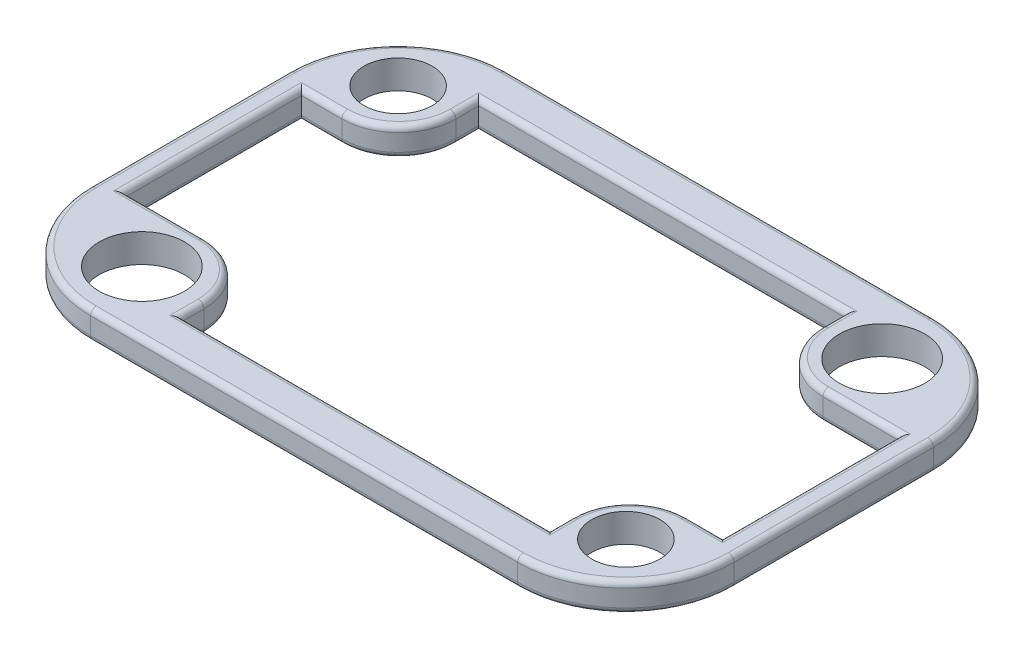
SolidWorks part; units mm, degrees
ref_plane "Alzado" through (0, 0, 0) normal (0, 0, 1) x (1, 0, 0)
ref_plane "Planta" through (0, 0, 0) normal (0, 1, 0) x (1, 0, 0)
ref_plane "Vista lateral" through (0, 0, 0) normal (1, 0, 0) x (0, 0, -1)
sketch "Sketch1" plane through (0, 0, 0) normal (0, 1, 0) x (1, 0, 0)
  line L1 (-57.5, 37.5) -> (57.5, 37.5)
  line L2 (-57.5, 37.5) -> (-57.5, -37.5)
  line L3 (-57.5, -37.5) -> (57.5, -37.5)
  line L4 (57.5, 37.5) -> (57.5, -37.5)
  circle A0 centre (-44.48, 24.48) radius 6
  circle A1 centre (44.48, -24.48) radius 6
  point P0 (0, 0)
  dimension "D6" = 12
  dimension "D10" = 12
  dimension "D1" = 75
  dimension "D2" = 115
  dimension "D3" = 37.5
  dimension "D4" = 57.5
  dimension "D5" = 13.02
  dimension "D7" = 13.02
  dimension "D8" = 13.02
  dimension "D9" = 13.02
extrude "Boss-Extrude1" add sketch "Sketch1" along normal blind 5
sketch "Sketch2" plane through (0, 5, 0) normal (0, 1, 0) x (1, 0, 0)
  line L0 (57.5, 37.5) -> (-57.5, 37.5) construction
  line L1 (-57.5, 37.5) -> (-57.5, -37.5) construction
  line L2 (57.5, -37.5) -> (57.5, 37.5) construction
  line L4 (-57.3874, 0) -> (58.0842, 0) construction
  line L5 (-41.5, 15.5) -> (41.5, 15.5)
  line L6 (-51.5, 5.5) -> (-51.5, -5.5)
  line L7 (-41.5, -15.5) -> (41.5, -15.5)
  line L8 (51.5, 5.5) -> (51.5, -5.5)
  line L9 (-51.5, 15.5) -> (51.5, -15.5) construction
  line L10 (-51.5, -15.5) -> (51.5, 15.5) construction
  arc A5 (41.5, -15.5) -> (51.5, -5.5) centre (41.5, -5.5) ccw
  arc A6 (41.5, 15.5) -> (51.5, 5.5) centre (41.5, 5.5) cw
  arc A7 (-51.5, -5.5) -> (-41.5, -15.5) centre (-41.5, -5.5) ccw
  arc A8 (-41.5, 15.5) -> (-51.5, 5.5) centre (-41.5, 5.5) ccw
  point P19 (0, 0)
  dimension "D18" = 10
  dimension "D15" = 6
  dimension "D16" = 6
  dimension "D17" = 22
extrude "Cut-Extrude1" cut sketch "Sketch2" against normal blind 5
fillet "Fillet1" radius 20 4 edges at (-57.5, 2.5, 37.5) (-57.5, 2.5, -37.5) (57.5, 2.5, -37.5) (57.5, 2.5, 37.5)
sketch "Sketch5" plane through (0, 0, 0) normal (0, -1, 0) x (1, 0, 0)
  line L0 (-37.5, 37.5) -> (37.5, 37.5) construction
  line L1 (-57.5, -17.5) -> (-57.5, 17.5) construction
  line L2 (37.5, -37.5) -> (-37.5, -37.5) construction
  line L3 (57.5, 17.5) -> (57.5, -17.5) construction
  circle A0 centre (-39.5, 25.5) radius 7.5
  circle A1 centre (39.5, -25.5) radius 7.5
  dimension "D5" = 15
  dimension "D6" = 15
  dimension "D1" = 12
  dimension "D2" = 18
  dimension "D3" = 12
  dimension "D4" = 18
extrude "Cut-Extrude4" cut sketch "Sketch5" against normal blind 10
sketch "Sketch8" plane through (0, 0, 0) normal (0, -1, 0) x (1, 0, 0)
sketch "Sketch9" plane through (0, 5, 0) normal (0, 1, 0) x (1, 0, 0)
  line L0 (41.5, 15.5) -> (-41.5, 15.5) construction
  line L1 (-35.3608, 15.5) -> (29.1011, 15.5)
  line L2 (-35.3608, 15.5) -> (-35.3608, 29.5)
  line L3 (-35.3608, 29.5) -> (29.1011, 29.5)
  line L4 (29.1011, 15.5) -> (29.1011, 29.5)
  line L5 (-41.5, -15.5) -> (41.5, -15.5) construction
  line L6 (-28.6067, -15.5) -> (36.1733, -15.5)
  line L7 (-28.6067, -15.5) -> (-28.6067, -29.5)
  line L8 (-28.6067, -29.5) -> (36.1733, -29.5)
  line L9 (36.1733, -15.5) -> (36.1733, -29.5)
  line L10 (-37.5, -37.5) -> (37.5, -37.5) construction
  line L11 (29.1011, 15.5) -> (52.5, 15.5)
  line L12 (29.1011, 15.5) -> (29.1011, -15.5)
  line L13 (29.1011, -15.5) -> (52.5, -15.5)
  line L14 (52.5, 15.5) -> (52.5, -15.5)
  line L15 (-28.6067, 15.5) -> (-52.5, 15.5)
  line L16 (-28.6067, 15.5) -> (-28.6067, -15.5)
  line L17 (-28.6067, -15.5) -> (-52.5, -15.5)
  line L18 (-52.5, 15.5) -> (-52.5, -15.5)
  line L19 (-57.5, 17.5) -> (-57.5, -17.5) construction
  line L20 (57.5, -17.5) -> (57.5, 17.5) construction
  line L21 (37.5, 37.5) -> (-37.5, 37.5) construction
  point P26 (-35.3608, 22.5)
  dimension "D1" = 8
  dimension "D2" = 31
  dimension "D3" = 5
  dimension "D4" = 5
  dimension "D5" = 8
  dimension "D6" = 64.78
  dimension "D7" = 14
  dimension "D8" = 64.4619
  dimension "D9" = 64.4619
  dimension "D10" = 23.3989
  dimension "D11" = 28.3989
  dimension "D12" = 28.6067
  dimension "D13" = 32.9715
extrude "Cut-Extrude5" cut sketch "Sketch9" against normal blind 10 contours L2 L1 L4 L3 | L16 L15 L18 L17 | L7 L6 L9 L8 | L12 L11 L14 L13
fillet "Fillet2" radius 10 4 edges at (36.1733, 2.5, 15.5) (-28.6067, 2.5, 15.5) (-35.3608, 2.5, -15.5) (29.1011, 2.5, -15.5)
sketch "Sketch11" plane through (0, 5, 0) normal (0, 1, 0) x (1, 0, 0)
  line L0 (57.5, -17.5) -> (57.5, 17.5) construction
  line L1 (-37.5, -37.5) -> (37.5, -37.5) construction
  line L2 (-57.5, 17.5) -> (-57.5, -17.5) construction
  line L3 (37.5, 37.5) -> (-37.5, 37.5) construction
  line L4 (57.5, -17.5) -> (57.5, 17.5)
  line L5 (-37.5, -37.5) -> (37.5, -37.5)
  line L6 (-57.5, 17.5) -> (-57.5, -17.5)
  line L7 (37.5, 37.5) -> (-37.5, 37.5)
  line L8 (37.5, 36.5) -> (-37.5, 36.5)
  line L9 (-56.5, 17.5) -> (-56.5, -17.5)
  line L10 (-37.5, -36.5) -> (37.5, -36.5)
  line L11 (56.5, -17.5) -> (56.5, 17.5)
  arc A0 (57.5, 17.5) -> (37.5, 37.5) centre (37.5, 17.5) ccw construction
  arc A1 (37.5, -37.5) -> (57.5, -17.5) centre (37.5, -17.5) ccw construction
  arc A2 (-57.5, -17.5) -> (-37.5, -37.5) centre (-37.5, -17.5) ccw construction
  arc A3 (-37.5, 37.5) -> (-57.5, 17.5) centre (-37.5, 17.5) ccw construction
  arc A4 (57.5, 17.5) -> (37.5, 37.5) centre (37.5, 17.5) ccw
  arc A5 (37.5, -37.5) -> (57.5, -17.5) centre (37.5, -17.5) ccw
  arc A6 (-57.5, -17.5) -> (-37.5, -37.5) centre (-37.5, -17.5) ccw
  arc A7 (-37.5, 37.5) -> (-57.5, 17.5) centre (-37.5, 17.5) ccw
  arc A8 (-37.5, 36.5) -> (-56.5, 17.5) centre (-37.5, 17.5) ccw
  arc A9 (-56.5, -17.5) -> (-37.5, -36.5) centre (-37.5, -17.5) ccw
  arc A10 (37.5, -36.5) -> (56.5, -17.5) centre (37.5, -17.5) ccw
  arc A11 (56.5, 17.5) -> (37.5, 36.5) centre (37.5, 17.5) ccw
  dimension "D1" = 1
extrude "Cut-Extrude7" cut sketch "Sketch11" against normal blind 16 contours A4 L7 A7 L6 A6 L5 A5 L4 | L8 A8 L9 A9 L10 A10 L11 A11
fillet "Fillet3" radius 1 48 edges at (29.1011, 0, -27.5) (32.03, 0, -18.4289) (36.1733, 0, 27.5) (49.3367, 0, 15.5) (-28.6067, 0, 27.5) (-31.5356, 0, 18.4289) (-35.3608, 0, -27.5) (-38.2898, 0, -18.4289) (49.3367, 5, 15.5) (36.1733, 5, 27.5) (29.1011, 5, -27.5) (45.8005, 5, -15.5) (-35.3608, 5, -27.5) (-38.2898, 5, -18.4289) (-28.6067, 5, 27.5) (-31.5356, 5, 18.4289) (-50.935, 5, -30.935) (0, 5, -36.5) (50.935, 5, -30.935) (56.5, 5, 0) (50.935, 5, 30.935) (0, 5, 36.5) (-50.935, 5, 30.935) (-50.935, 0, 30.935) (-56.5, 0, 0) (-50.935, 0, -30.935) (0, 0, -36.5) (50.935, 0, -30.935) (56.5, 0, 0) (50.935, 0, 30.935) (-3.1299, 0, -29.5) (45.8005, 0, -15.5) (52.5, 0, 0) (39.1022, 0, 18.4289) (3.7833, 0, 29.5) (-45.5533, 0, 15.5) (-52.5, 0, 0) (-48.9304, 0, -15.5) (-3.1299, 5, -29.5) (52.5, 5, 0) (39.1022, 5, 18.4289) (32.03, 5, -18.4289) (-48.9304, 5, -15.5) (3.7833, 5, 29.5) (-45.5533, 5, 15.5) (-52.5, 5, 0) (-56.5, 5, 0) (0, 0, 36.5)
